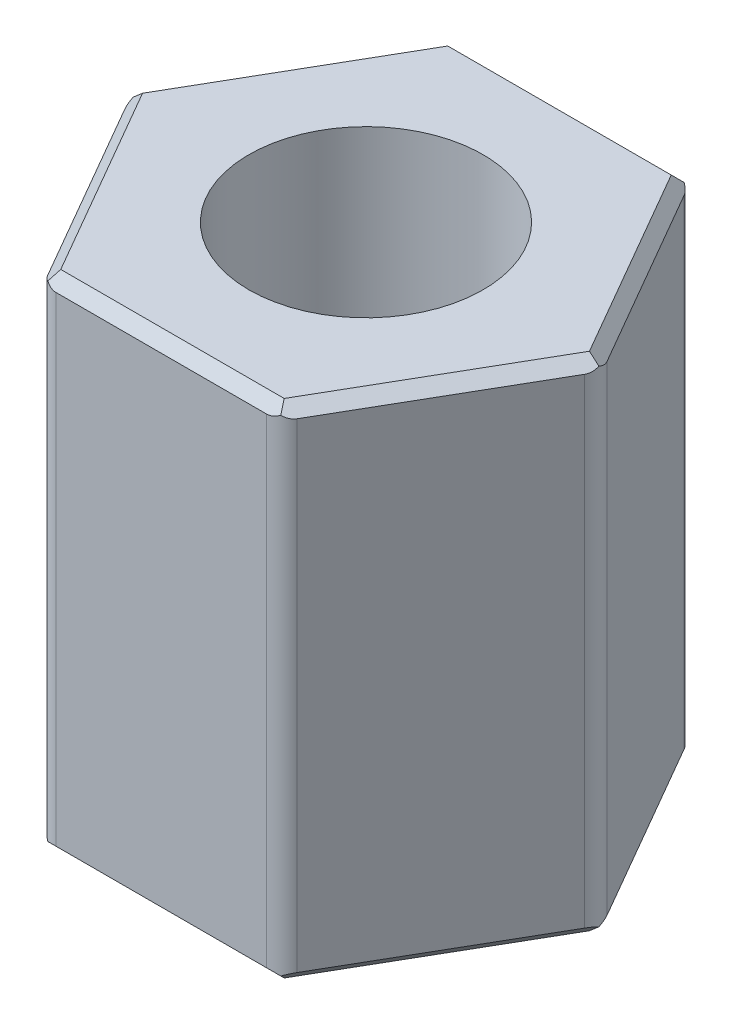
SolidWorks part; units mm, degrees
ref_plane "Front Plane" through (0, 0, 0) normal (0, 0, 1) x (1, 0, 0)
ref_plane "Top Plane" through (0, 0, 0) normal (0, 1, 0) x (1, 0, 0)
ref_plane "Right Plane" through (0, 0, 0) normal (1, 0, 0) x (0, 0, -1)
sketch "Sketch1" plane through (0, 0, 0) normal (0, 1, 0) x (1, 0, 0)
  line L1 (2.691, -4.6609) -> (5.3819, 0)
  line L2 (5.3819, 0) -> (2.691, 4.6609)
  line L3 (2.691, 4.6609) -> (-2.691, 4.6609)
  line L4 (-2.691, 4.6609) -> (-5.3819, 0)
  line L5 (-5.3819, 0) -> (-2.691, -4.6609)
  line L6 (-2.691, -4.6609) -> (2.691, -4.6609)
  circle A0 centre (0, 0) radius 4.6609 construction
  circle A1 centre (0, 0) radius 2.667
  dimension "D1" = 9.3218
  dimension "D2" = 5.334
extrude "Boss-Extrude1" add sketch "Sketch1" along normal blind 11.43
chamfer "Chamfer1" distance 0.254 angle 45 18 edges at (4.0365, 0, 2.3305) (4.0365, 0, -2.3305) (0, 0, -4.6609) (-4.0365, 0, -2.3305) (-4.0365, 0, 2.3304) (0, 0, 4.6609) (-2.691, 5.715, -4.6609) (-5.3819, 5.715, 0) (-2.691, 5.715, 4.6609) (2.691, 5.715, 4.6609) (5.3819, 5.715, 0) (2.691, 5.715, -4.6609) (-4.0365, 11.43, -2.3305) (0, 11.43, -4.6609) (4.0365, 11.43, -2.3305) (-4.0365, 11.43, 2.3304) (0, 11.43, 4.6609) (4.0365, 11.43, 2.3305)
fillet "Fillet1" radius 0.508 6 edges at (5.3819, 5.715, 0) (2.691, 5.715, 4.6609) (-2.691, 5.715, 4.6609) (-5.3819, 5.715, 0) (-2.691, 5.715, -4.6609) (2.691, 5.715, -4.6609)
